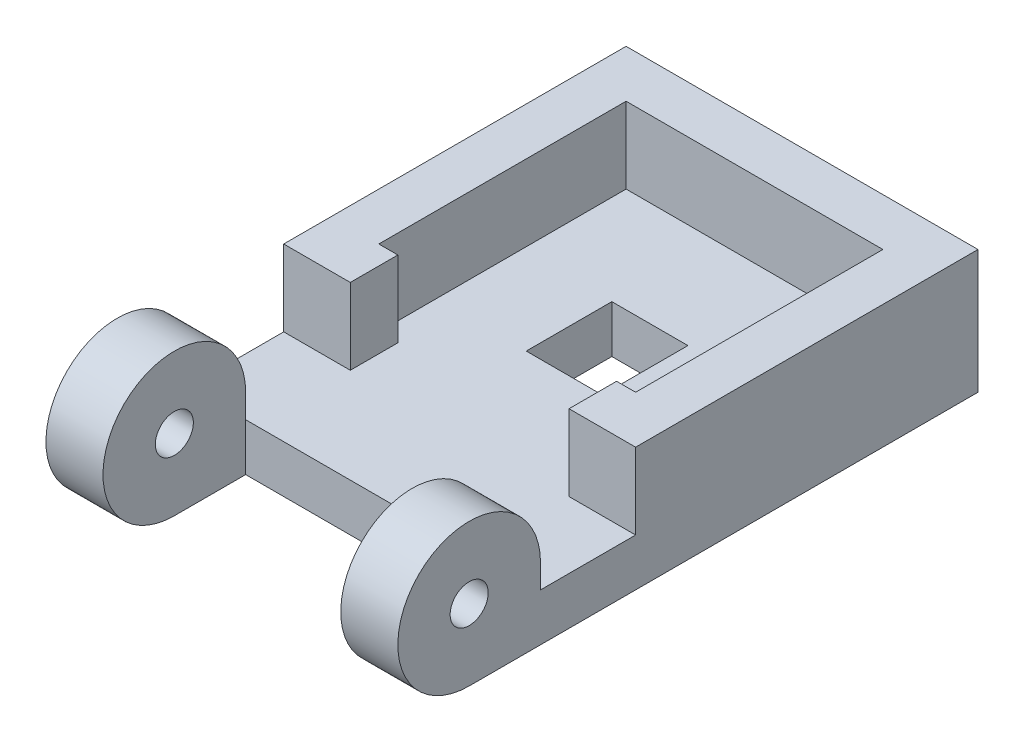
SolidWorks part; units mm, degrees
ref_plane "Ebene vorne" through (0, 0, 0) normal (0, 0, 1) x (1, 0, 0)
ref_plane "Ebene oben" through (0, 0, 0) normal (0, 1, 0) x (1, 0, 0)
ref_plane "Ebene rechts" through (0, 0, 0) normal (1, 0, 0) x (0, 0, -1)
sketch "Skizze1" plane through (0, 0, 0) normal (0, 1, 0) x (1, 0, 0)
  line L1 (-4, -4.5) -> (4, -4.5)
  line L2 (-4, -4.5) -> (-4, 4.5)
  line L3 (-4, 4.5) -> (4, 4.5)
  line L4 (4, -4.5) -> (4, 4.5)
  line L5 (-4, -4.5) -> (4, 4.5) construction
  line L6 (-4, 4.5) -> (4, -4.5) construction
  line L7 (12.5, -9.5) -> (-12.5, -9.5)
  line L8 (12.5, -9.5) -> (12.5, 14.5)
  line L9 (12.5, 14.5) -> (-12.5, 14.5)
  line L10 (-12.5, -9.5) -> (-12.5, 14.5)
  line L11 (12.5, -9.5) -> (-12.5, 14.5) construction
  line L12 (12.5, 14.5) -> (-12.5, -9.5) construction
  line L17 (-17.5, -14.5) -> (17.5, 19.5) construction
  line L18 (-17.5, 19.5) -> (17.5, -14.5) construction
  line L19 (-18.5, 20.5) -> (18.5, 20.5)
  line L20 (-18.5, 20.5) -> (-18.5, -25.5)
  line L21 (-18.5, -25.5) -> (18.5, -25.5)
  line L22 (18.5, 20.5) -> (18.5, -25.5)
  point P0 (0, 0)
  point P6 (0, 2.5)
  point P11 (0, 2.5)
  dimension "D1" = 9
  dimension "D2" = 8
  dimension "D3" = 24
  dimension "D4" = 10
  dimension "D5" = 8.5
  dimension "D6" = 8.5
  dimension "D7" = 6
  dimension "D8" = 6
  dimension "D9" = 6
  dimension "D10" = 16
extrude "Aufsatz-Linear austragen2" add sketch "Skizze1" along normal blind 5 contours L10 L7 L8 L9 L4 L1 L2 L3 | L22 L19 L20 L21 L7 L10 L9 L8
sketch "Skizze2" plane through (0, 5, 0) normal (0, 1, 0) x (1, 0, 0)
  line L0 (-18.5, 20.5) -> (-18.5, -25.5) construction
  line L1 (-13.5, 15.5) -> (13.5, 15.5)
  line L2 (-13.5, 15.5) -> (-13.5, -10.5)
  line L3 (-13.5, -10.5) -> (13.5, -10.5)
  line L4 (13.5, 15.5) -> (13.5, -10.5)
  line L5 (-18.5, 20.5) -> (18.5, 20.5)
  line L6 (-18.5, 20.5) -> (-18.5, -25.5)
  line L7 (-18.5, -25.5) -> (18.5, -25.5)
  line L8 (18.5, 20.5) -> (18.5, -25.5)
  line L9 (-13.5, -10.5) -> (18.5, -10.5)
  line L10 (18.5, -10.5) -> (-18.5, -10.5)
  line L12 (-18.5, -10.5) -> (-11.5, -10.5)
  line L13 (-18.5, -10.5) -> (-18.5, -15.5)
  line L14 (-18.5, -15.5) -> (-11.5, -15.5)
  line L15 (-11.5, -10.5) -> (-11.5, -15.5)
  line L16 (18.5, -10.5) -> (11.5, -10.5)
  line L17 (18.5, -10.5) -> (18.5, -15.5)
  line L18 (18.5, -15.5) -> (11.5, -15.5)
  line L19 (11.5, -10.5) -> (11.5, -15.5)
  line M18 (18.5, 20.5) -> (-18.5, 20.5)
  line M19 (-18.5, 20.5) -> (-18.5, -25.5)
  dimension "D1" = 5
  dimension "D2" = 5
  dimension "D3" = 5
  dimension "D4" = 15
  dimension "D5" = 5
  dimension "D6" = 5
  dimension "D7" = 7
  dimension "D8" = 7
extrude "Aufsatz-Linear austragen3" add sketch "Skizze2" along normal blind 8 contours L10 L2 L1 L4 L9 L8 M18 M19 | L15 L3 L10 L6 L14 | L3 L19 L18 L8 L9
sketch "Skizze3" plane through (-18.5, 0, 0) normal (-1, 0, 0) x (0, 0, 1)
  line L0 (25.5, 7.5) -> (40.5, 7.5)
  line L1 (25.5, 0) -> (40.5, 0)
  line L2 (25.5, 0) -> (25.5, 15)
  line L3 (25.5, 15) -> (40.5, 15)
  line L4 (40.5, 0) -> (40.5, 15)
  circle A0 centre (33, 7.5) radius 7.5
  circle A1 centre (33, 7.5) radius 2
  line M7 (25.5, 0) -> (25.5, 5)
  dimension "D3" = 4
  dimension "D1" = 15
  dimension "D2" = 15
extrude "Aufsatz-Linear austragen4" add sketch "Skizze3" against normal blind 37 contours A0 L2 L1 M7 | A1 L0 A0 | A1 L0 A0
sketch "Skizze4" plane through (0, 5, 0) normal (0, 1, 0) x (1, 0, 0)
  line L0 (-18.5, -25.5) -> (18.5, -25.5) construction
  line L1 (-12.5, -25.5) -> (12.5, -25.5)
  line L2 (-12.5, -25.5) -> (-12.5, -40.5)
  line L3 (-12.5, -40.5) -> (12.5, -40.5)
  line L4 (12.5, -25.5) -> (12.5, -40.5)
  line L5 (-18.5, -40.5) -> (18.5, -40.5) construction
  line L6 (-18.5, -25.5) -> (-18.5, -40.5) construction
  dimension "D1" = 6
  dimension "D2" = 25
extrude "Schnitt-Linear austragen1" cut sketch "Skizze4" against normal blind 11 and the other way blind 22
